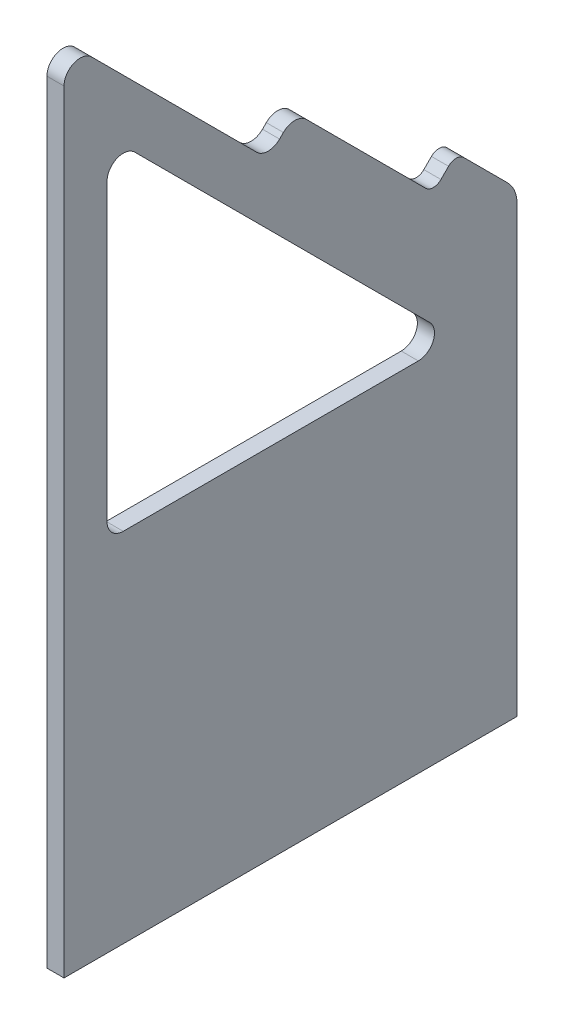
SolidWorks part; units mm, degrees
ref_plane "Plan de face" through (0, 0, 0) normal (0, 0, 1) x (1, 0, 0)
ref_plane "Plan de dessus" through (0, 0, 0) normal (0, 1, 0) x (1, 0, 0)
ref_plane "Plan de droite" through (0, 0, 0) normal (1, 0, 0) x (0, 0, -1)
sketch "Esquisse1" plane through (0, 0, 0) normal (1, 0, 0) x (0, 0, -1)
  line L0 (-42.0729, 0) -> (42.0729, 0)
  line L1 (42.0729, 0) -> (42.0729, 84.9497)
  line L2 (42.0729, 84.9497) -> (30.7591, 96.2635)
  line L3 (30.7591, 96.2635) -> (26.5165, 92.0208)
  line L4 (26.5165, 92.0208) -> (33.5876, 84.9497)
  line L5 (33.5876, 84.9497) -> (28.6378, 80)
  line L6 (28.6378, 80) -> (-42.0729, 150.7107)
  line L7 (-42.0729, 150.7107) -> (-42.0729, 0)
  point P9 (30.052, 88.4853)
  point P12 (0, 0)
  dimension "D1" = 45
  dimension "D2" = 7
  dimension "D3" = 6
  dimension "D4" = 80
  dimension "D5" = 100
  dimension "D6" = 10
extrude "Boss.-Extru.1" add sketch "Esquisse1" along normal blind 3.175
sketch "Esquisse2" plane through (3.175, 0, 0) normal (1, 0, 0) x (0, 0, -1)
  line L0 (-42.0729, 0) -> (42.0729, 0) construction
  line L1 (-10, 0) -> (10, 0)
  line L2 (-10, 0) -> (-10, 6.35)
  line L3 (-10, 6.35) -> (10, 6.35)
  line L4 (10, 0) -> (10, 6.35)
  line L15 (-10, 52.7) -> (10, 52.7)
  line L16 (-10, 52.7) -> (-10, 46.35)
  line L17 (-10, 46.35) -> (10, 46.35)
  line L18 (10, 52.7) -> (10, 46.35)
  line L19 (42.0729, 0) -> (42.0729, 84.9497) construction
  line L29 (42.0729, 36.35) -> (35.7229, 36.35)
  line L30 (42.0729, 36.35) -> (42.0729, 16.35)
  line L31 (42.0729, 16.35) -> (35.7229, 16.35)
  line L32 (35.7229, 36.35) -> (35.7229, 16.35)
  point P6 (0, 0)
  point P22 (35.7229, 26.35)
  dimension "D1" = 20
  dimension "D3" = 6.35
  dimension "D5" = 40
  dimension "D6" = 26.35
fillet "Congé1" radius 6 1 edges at (1.5875, 84.9497, -42.0729)
fillet "Congé2" radius 2 2 edges at (1.5875, 92.0208, -26.5165) (1.5875, 96.2635, -30.7591)
sketch "Esquisse4" plane through (3.175, 0, 0) normal (1, 0, 0) x (0, 0, -1)
  line L0 (30.9741, 66.35) -> (-34.0729, 66.35)
  line L1 (-34.0729, 66.35) -> (-34.0729, 131.397)
  line L2 (-34.0729, 131.397) -> (30.9741, 66.35)
  line L3 (28.6378, 80) -> (-42.0729, 150.7107) construction
  line L4 (-42.0729, 150.7107) -> (-42.0729, 0) construction
  dimension "D1" = 8
  dimension "D2" = 8
  dimension "D3" = 65.047
extrude "Enlèv. mat.-Extru.2" cut sketch "Esquisse4" against normal through all
fillet "Congé4" radius 3 4 edges at (1.5875, 66.35, -30.9741) (1.5875, 66.35, 34.0729) (1.5875, 131.397, 34.0729) (1.5875, 150.7107, 42.0729)
sketch "Esquisse5" plane through (3.175, 0, 0) normal (1, 0, 0) x (0, 0, -1)
  line L0 (27.9307, 90.6066) -> (33.5876, 84.9497) construction
  line L1 (30.7591, 96.2635) -> (26.5165, 92.0208)
  line L2 (26.5165, 92.0208) -> (0.7929, 117.7444)
  line L3 (0.7929, 117.7444) -> (-4.1569, 112.7947)
  line L4 (28.6378, 80) -> (-36.9515, 145.5894) construction
  line L5 (40.3155, 86.7071) -> (32.1734, 94.8492) construction
  line L6 (-4.1569, 112.7947) -> (28.6378, 80)
  line L7 (28.6378, 80) -> (37.8302, 89.1924)
  line L8 (37.8302, 89.1924) -> (30.7591, 96.2635)
  line L9 (29.3449, 94.8492) -> (27.9307, 93.435) construction
  point P3 (-4.1569, 112.7947)
extrude "Boss.-Extru.2" add sketch "Esquisse5" against normal up to surface (3.175 mm away) up to face at (0, 87.3887, 13.0341)
fillet "Congé5" radius 2 2 edges at (1.5875, 92.0208, -26.5165) (1.5875, 96.2635, -30.7591)
fillet "Congé6" radius 3 2 edges at (1.5875, 112.7947, 4.1569) (1.5875, 117.7444, -0.7929)
